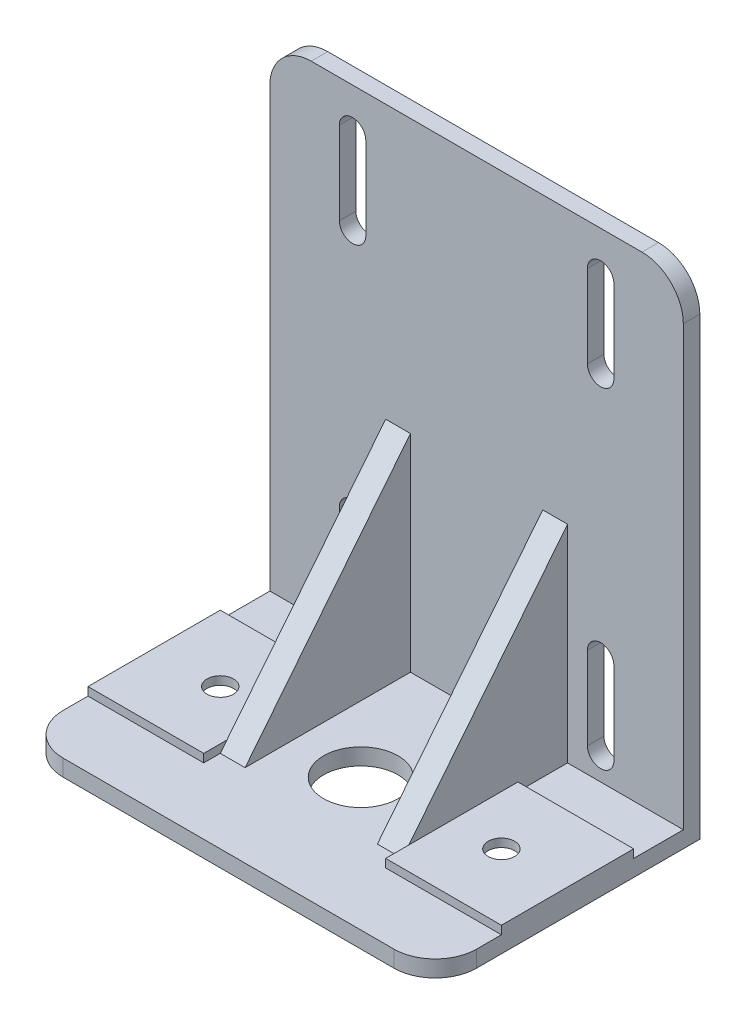
SolidWorks part; units mm, degrees
ref_plane "Płaszczyzna przednia" through (0, 0, 0) normal (0, 0, 1) x (1, 0, 0)
ref_plane "Płaszczyzna górna" through (0, 0, 0) normal (0, 1, 0) x (1, 0, 0)
ref_plane "Płaszczyzna prawa" through (0, 0, 0) normal (1, 0, 0) x (0, 0, -1)
sketch "Szkic1" plane through (0, 0, 0) normal (0, 0, 1) x (1, 0, 0)
  line L1 (-25, -30) -> (25, -30)
  line L2 (-25, -30) -> (-25, 25)
  line L3 (-20, 30) -> (20, 30)
  line L4 (25, -30) -> (25, 25)
  line L5 (-25, -30) -> (25, 30) construction
  line L6 (-25, 30) -> (25, -30) construction
  arc A2 (25, 25) -> (20, 30) centre (20, 25) ccw
  arc A3 (-20, 30) -> (-25, 25) centre (-20, 25) ccw
  point P0 (0, 0)
  point P5 (0, 0)
  point P8 (0, 0)
  point P18 (0, 0)
  dimension "D1" = 60
  dimension "D2" = 50
extrude "Dodanie-wyciągnięcie1" add sketch "Szkic1" along normal blind 2
sketch "Szkic2" plane through (0, 0, 2) normal (0, 0, 1) x (1, 0, 0)
  line L0 (0, 30) -> (0, -30) construction
  line L1 (20, 30) -> (-20, 30) construction
  line L2 (-25, -30) -> (25, -30) construction
  line L3 (25, 0) -> (-25, 0) construction
  line L6 (-15, 25) -> (-15, 15) construction
  line L7 (-13.4, 25) -> (-13.4, 15)
  line L8 (-16.6, 25) -> (-16.6, 15)
  line L9 (15, 25) -> (15, 15) construction
  line L10 (13.4, 25) -> (13.4, 15)
  line L11 (16.6, 25) -> (16.6, 15)
  line L12 (15, -25) -> (15, -15) construction
  line L13 (13.4, -25) -> (13.4, -15)
  line L14 (16.6, -25) -> (16.6, -15)
  line L15 (-15, -25) -> (-15, -15) construction
  line L16 (-13.4, -25) -> (-13.4, -15)
  line L17 (-16.6, -25) -> (-16.6, -15)
  line L18 (25, -30) -> (25, 25) construction
  line L19 (-25, 25) -> (-25, -30) construction
  arc A0 (-13.4, 25) -> (-16.6, 25) centre (-15, 25) ccw
  arc A1 (-16.6, 15) -> (-13.4, 15) centre (-15, 15) ccw
  arc A2 (13.4, 25) -> (16.6, 25) centre (15, 25) cw
  arc A3 (16.6, 15) -> (13.4, 15) centre (15, 15) cw
  arc A4 (13.4, -25) -> (16.6, -25) centre (15, -25) ccw
  arc A5 (16.6, -15) -> (13.4, -15) centre (15, -15) ccw
  arc A6 (-13.4, -25) -> (-16.6, -25) centre (-15, -25) cw
  arc A7 (-16.6, -15) -> (-13.4, -15) centre (-15, -15) cw
  point P14 (-15, 20)
  point P21 (15, 20)
  point P28 (15, -20)
  point P35 (-15, -20)
  point P40 (0, 0)
  point P42 (0, 0)
  point P43 (0, 0)
  dimension "D1" = 3.2
  dimension "D2" = 10
  dimension "D3" = 15
  dimension "D4" = 30
  dimension "D5" = 20
  dimension "D6" = 20
extrude "Wytnij-wyciągnięcie1" cut sketch "Szkic2" against normal up to next
sketch "Szkic4" plane through (0, 0, 2) normal (0, 0, 1) x (1, 0, 0)
  line L0 (25, -30) -> (25, 25) construction
  line L1 (-25, -30) -> (25, -30)
  line L2 (-25, -30) -> (-25, -28)
  line L3 (-25, -28) -> (25, -28)
  line L4 (25, -30) -> (25, -28)
  dimension "D1" = 2
extrude "Dodanie-wyciągnięcie2" add sketch "Szkic4" along normal blind 30
sketch "Szkic6" plane through (-25, 0, 0) normal (-1, 0, 0) x (0, 0, 1)
  line L0 (2, -28) -> (2, -3)
  line L1 (2, 25) -> (2, -28) construction
  line L2 (2, -3) -> (22, -28)
  line L3 (32, -28) -> (2, -28) construction
  line L4 (22, -28) -> (2, -28)
  dimension "D1" = 25
  dimension "D2" = 20
extrude "Dodanie-wyciągnięcie3" add sketch "Szkic6" against normal blind 3 from offset 14 separate body offset against normal yes
mirror "Lustro3" about plane through (0, 0, 0) normal (1, 0, 0) of "Dodanie-wyciągnięcie3"
fillet "Zaokrąglenie1" radius 5 2 edges at (25, -29, 32) (-25, -29, 32)
sketch "Szkic7" plane through (0, -30, 0) normal (0, -1, 0) x (1, 0, 0)
  line L0 (0, 0) -> (0, 32) construction
  line L1 (-25, 0) -> (25, 0) construction
  line L2 (-20, 32) -> (20, 32) construction
  circle A0 centre (0, 16) radius 4.5
  circle A1 centre (-17, 16) radius 4.5
  circle A2 centre (17, 16) radius 4.5
  point P12 (0, 0)
  dimension "D1" = 9
  dimension "D2" = 17
  dimension "D3" = 17
extrude "Wytnij-wyciągnięcie2" cut sketch "Szkic7" against normal blind 2
sketch "Szkic8" plane through (0, -28, 0) normal (0, 1, 0) x (1, 0, 0)
  line L0 (-25, -27) -> (-25, -2) construction
  line L1 (-25, -24) -> (-11, -24)
  line L2 (-25, -24) -> (-25, -8)
  line L3 (-25, -8) -> (-11, -8)
  line L4 (-11, -24) -> (-11, -8)
  line L5 (-11, -22) -> (-11, -2) construction
  line L6 (0, 0) -> (0, -32) construction
  line L7 (20, -32) -> (-20, -32) construction
  line L8 (20, 0) -> (-20, 0) construction
  line L9 (25, -8) -> (11, -8)
  line L10 (11, -24) -> (11, -8)
  line L11 (25, -24) -> (11, -24)
  line L12 (25, -24) -> (25, -8)
  circle A0 centre (-17, -16) radius 1.6
  circle A1 centre (17, -16) radius 1.6
  dimension "D3" = 3.2
  dimension "D1" = 8
  dimension "D2" = 8
extrude "Dodanie-wyciągnięcie4" add sketch "Szkic8" along normal blind 1
